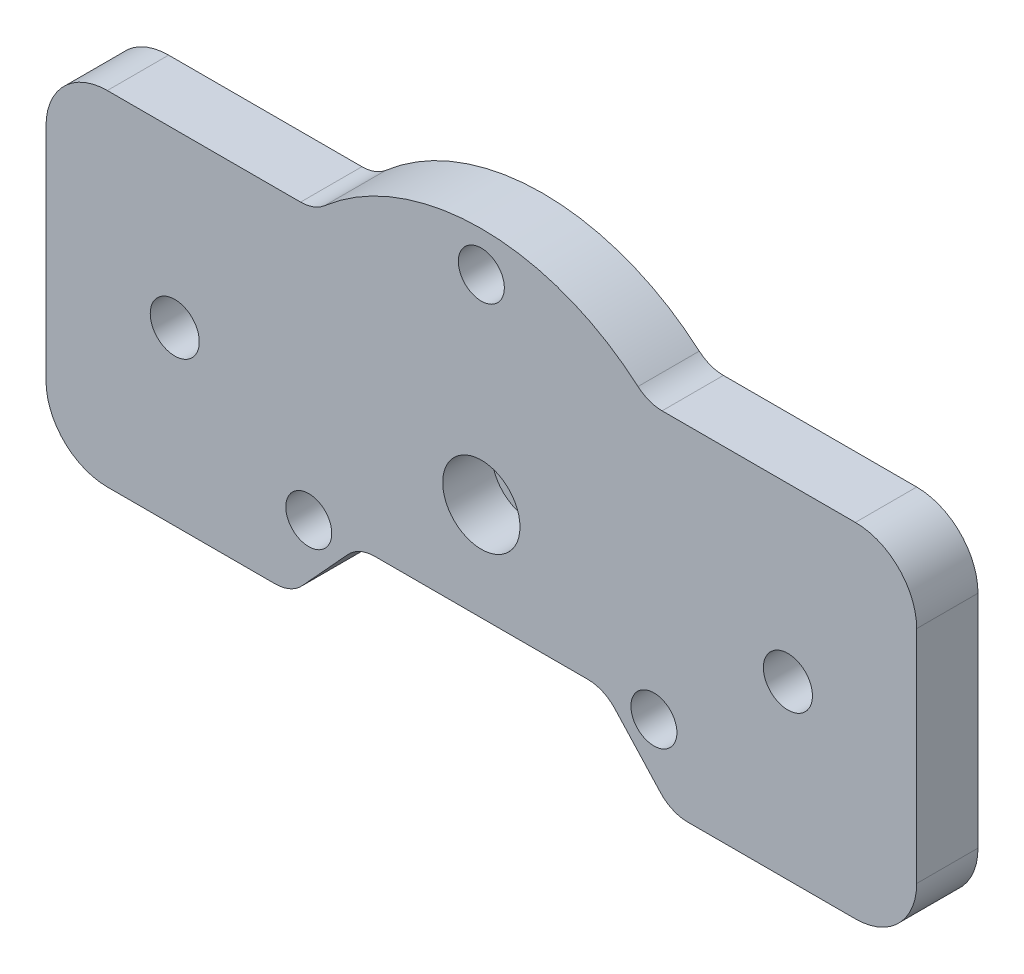
SolidWorks part; units mm, degrees
material "1060-H16"
ref_plane "Спереди" through (0, 0, 0) normal (0, 0, 1) x (1, 0, 0)
ref_plane "Сверху" through (0, 0, 0) normal (0, 1, 0) x (1, 0, 0)
ref_plane "Справа" through (0, 0, 0) normal (1, 0, 0) x (0, 0, -1)
sketch "Эскиз1" plane through (0, 0, 0) normal (0, 0, 1) x (1, 0, 0)
  line L0 (0, 28) -> (71, 0) construction
  line L1 (0, 0) -> (20, 0)
  line L2 (0, 0) -> (0, 28)
  line L3 (0, 28) -> (21.9261, 28)
  line L4 (71, 0) -> (71, 28)
  line L5 (71, 28) -> (0, 0) construction
  line L6 (0, 14) -> (71, 14) construction
  line L7 (49.0739, 28) -> (71, 28)
  line L8 (51, 0) -> (45.5, 6.0064)
  line L9 (45.5, 6.0064) -> (25.5, 6.0064)
  line L10 (25.5, 6.0064) -> (20, 0)
  line L11 (51, 0) -> (71, 0)
  circle A0 centre (35.5, 30.25) radius 1.875
  circle A1 centre (35.5, 14) radius 1.25
  arc A2 (49.0739, 28) -> (21.9261, 28) centre (35.5, 14) ccw
  circle A3 centre (43.625, 28.0729) radius 1.875 [skipped]
  circle A4 centre (49.5729, 22.125) radius 1.875 [skipped]
  circle A5 centre (51.75, 14) radius 1.875 [skipped]
  circle A6 centre (49.5729, 5.875) radius 1.875
  circle A7 centre (43.625, -0.0729) radius 1.875 [skipped]
  circle A8 centre (35.5, -2.25) radius 1.875 [skipped]
  circle A9 centre (27.375, -0.0729) radius 1.875 [skipped]
  circle A10 centre (21.4271, 5.875) radius 1.875
  circle A11 centre (19.25, 14) radius 1.875 [skipped]
  circle A12 centre (21.4271, 22.125) radius 1.875 [skipped]
  circle A13 centre (27.375, 28.0729) radius 1.875 [skipped]
  point P42 (35.5, 14)
  dimension "D3" = 20
  dimension "D5" = 3.75
  dimension "D7" = 2.5
  dimension "D1" = 71
  dimension "D2" = 28
  dimension "D4" = 20
  dimension "D6" = 16.25
  dimension "D8" = 12
extrude "Бобышка-Вытянуть1" add sketch "Эскиз1" along normal blind 5
fillet "Скругление1" radius 3 4 edges at (21.9261, 28, 2.5) (49.0739, 28, 2.5) (45.5, 6.0064, 2.5) (25.5, 6.0064, 2.5)
fillet "Скругление2" radius 5 4 edges at (0, 0, 2.5) (71, 0, 2.5) (71, 28, 2.5) (0, 28, 2.5)
fillet "Скругление3" radius 3 2 edges at (51, 0, 2.5) (20, 0, 2.5)
sketch "Эскиз2" plane through (0, 0, 5) normal (0, 0, 1) x (1, 0, 0)
  circle A0 centre (35.5, 14) radius 3.15
  dimension "D1" = 6.3
extrude "Вырез-Вытянуть1" cut sketch "Эскиз2" against normal blind 4
sketch "Эскиз3" plane through (0, 0, 0) normal (0, 0, -1) x (-1, 0, 0)
  line L0 (0, 14) -> (-71, 14) construction
  line L1 (0, 23) -> (0, 5) construction
  line L2 (-71, 5) -> (-71, 23) construction
  line L3 (-35.5, 6.0064) -> (-35.5, 33.5) construction
  line L4 (-26.8207, 6.0064) -> (-44.1793, 6.0064) construction
  circle A1 centre (-10.5, 14) radius 2
  circle A2 centre (-60.5, 14) radius 2
  arc A4 (-22.7259, 28.7333) -> (-48.2741, 28.7333) centre (-35.5, 14) ccw construction
  dimension "D3" = 25
  dimension "D4" = 50
extrude "Вырез-Вытянуть2" cut sketch "Эскиз3" against normal through all
